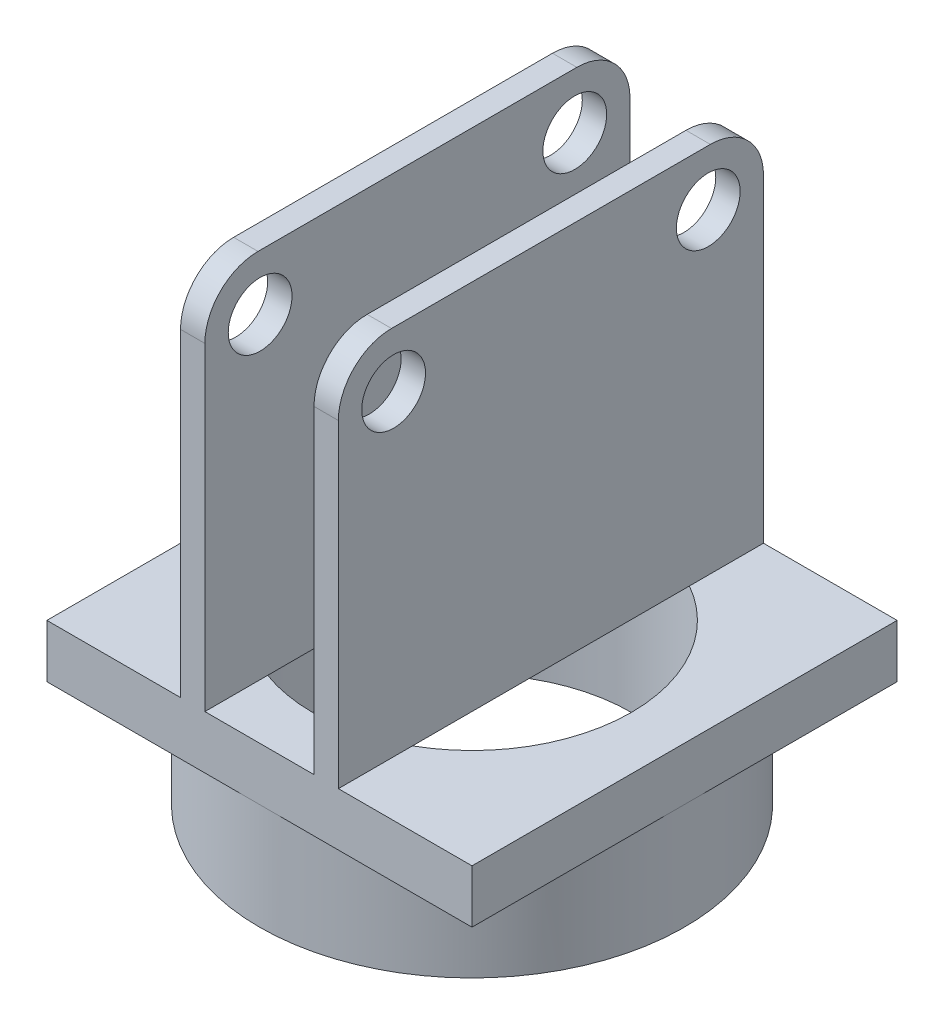
SolidWorks part; units mm, degrees
ref_plane "Front Plane" through (0, 0, 0) normal (0, 0, 1) x (1, 0, 0)
ref_plane "Top Plane" through (0, 0, 0) normal (0, 1, 0) x (1, 0, 0)
ref_plane "Right Plane" through (0, 0, 0) normal (1, 0, 0) x (0, 0, -1)
sketch "Sketch1" plane through (0, 0, 0) normal (0, 1, 0) x (1, 0, 0)
  circle A0 centre (0, 0) radius 20
  circle A1 centre (0, 0) radius 15
extrude "Boss-Extrude1" add sketch "Sketch1" along normal blind 10 contours A0 | A1
sketch "Sketch3" plane through (0, 10, 0) normal (0, 1, 0) x (1, 0, 0)
  line L1 (-20, 20) -> (20, 20)
  line L2 (-20, 20) -> (-20, -20)
  line L3 (-20, -20) -> (20, -20)
  line L4 (20, 20) -> (20, -20)
  line L5 (-20, 20) -> (20, -20) construction
  line L6 (-20, -20) -> (20, 20) construction
  point P0 (0, 0)
  dimension "D1" = 40
  dimension "D2" = 40
extrude "Boss-Extrude2" add sketch "Sketch3" along normal blind 5 contours L2 L3 L4 L1
sketch "Sketch5" plane through (0, 10, 0) normal (0, -1, 0) x (1, 0, 0)
  circle A0 centre (0, 0) radius 15
extrude "Cut-Extrude1" cut sketch "Sketch5" against normal blind 5
sketch "Sketch6" plane through (0, 15, 0) normal (0, 1, 0) x (1, 0, 0)
  line L0 (-20, -20) -> (20, -20) construction
  point P0 (-9.9019, -20)
sketch "Sketch7" plane through (0, 15, 0) normal (0, 1, 0) x (1, 0, 0)
  line L0 (-20, -20) -> (20, -20) construction
  line L5 (7.4268, 20) -> (-7.4268, 20)
  line L6 (7.4268, 20) -> (7.4268, -20)
  line L7 (7.4268, -20) -> (-7.4268, -20)
  line L8 (-7.4268, 20) -> (-7.4268, -20)
  line L9 (7.4268, 20) -> (-7.4268, -20) construction
  line L10 (7.4268, -20) -> (-7.4268, 20) construction
  point P0 (0, 0)
  point P1 (0, 0)
extrude "Boss-Extrude3" add sketch "Sketch7" along normal blind 35
fillet "Fillet1" radius 5 1 edges at (0, 50, 20)
fillet "Fillet2" radius 5 1 edges at (0, 50, -20)
sketch "Sketch8" plane through (7.4268, 0, 0) normal (1, 0, 0) x (0, 0, -1)
  line L5 (14.8032, -44.773) -> (-14.8032, 44.773) construction
  line L6 (14.8032, 44.773) -> (-14.8032, -44.773) construction
  circle A0 centre (-14.8032, 44.773) radius 3
  circle A1 centre (14.8032, 44.773) radius 3
  point P0 (0, 0)
extrude "Cut-Extrude2" cut sketch "Sketch8" against normal blind 35
sketch "Sketch9" plane through (0, 50, 0) normal (0, 1, 0) x (1, 0, 0)
  line L1 (5.1334, 24.3367) -> (-5.1334, 24.3367)
  line L2 (5.1334, 24.3367) -> (5.1334, -24.3367)
  line L3 (5.1334, -24.3367) -> (-5.1334, -24.3367)
  line L4 (-5.1334, 24.3367) -> (-5.1334, -24.3367)
  line L5 (5.1334, 24.3367) -> (-5.1334, -24.3367) construction
  line L6 (5.1334, -24.3367) -> (-5.1334, 24.3367) construction
  point P0 (0, 0)
extrude "Cut-Extrude5" cut sketch "Sketch9" against normal blind 35
